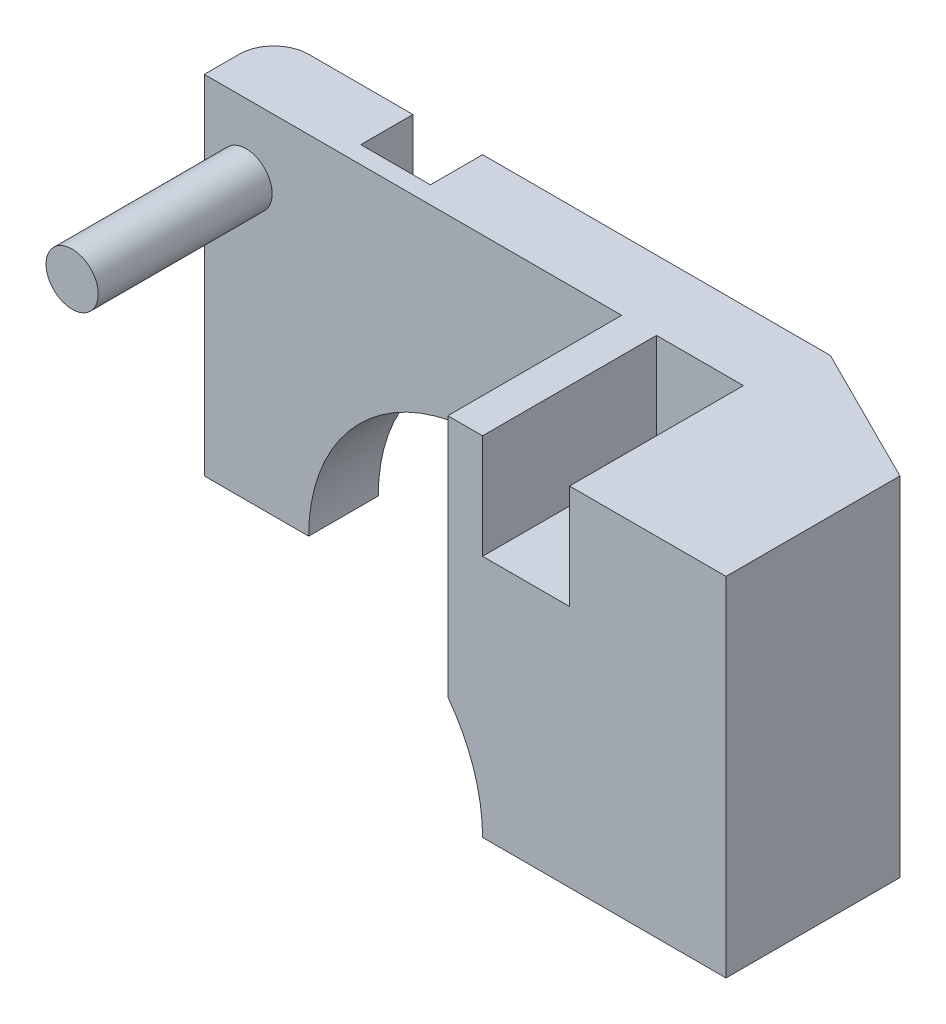
SolidWorks part; units mm, degrees
ref_plane "Přední rovina" through (0, 0, 0) normal (0, 0, 1) x (1, 0, 0)
ref_plane "Horní rovina" through (0, 0, 0) normal (0, 1, 0) x (1, 0, 0)
ref_plane "Pravá rovina" through (0, 0, 0) normal (1, 0, 0) x (0, 0, -1)
sketch "Skica1" plane through (0, 0, 0) normal (0, 0, 1) x (1, 0, 0)
  line L1 (0, 0) -> (200, 0)
  line L2 (0, 0) -> (0, 100)
  line L3 (0, 100) -> (200, 100)
  line L4 (200, 0) -> (200, 100)
  dimension "D1" = 100
  dimension "D2" = 200
extrude "Přidat vysunutím1" add sketch "Skica1" along normal blind 20
sketch "Skica2" plane through (0, 0, 20) normal (0, 0, 1) x (1, 0, 0)
  line L0 (0, 0) -> (200, 0) construction
  line L1 (120, 0) -> (200, 0)
  line L2 (120, 0) -> (120, 100)
  line L3 (120, 100) -> (130, 100)
  line L6 (0, 100) -> (0, 0) construction
  line L7 (155, 100) -> (200, 100)
  line L9 (130, 100) -> (130, 70)
  line L10 (130, 70) -> (155, 70)
  line L11 (155, 100) -> (155, 70)
  line L12 (200, 0) -> (200, 100)
  dimension "D1" = 120
  dimension "D3" = 10
  dimension "D5" = 30
extrude "Přidat vysunutím2" add sketch "Skica2" along normal blind 50 contours L9 L10 L11 L7 L12 L1 L2 L3
sketch "Skica4" plane through (0, 0, 0) normal (0, 0, -1) x (-1, 0, 0)
  line L0 (0, 0) -> (-200, 0) construction
  circle A0 centre (-80, 0) radius 50
  dimension "D1" = 100
  dimension "D2" = 80
extrude "Odebrat vysunutím1" cut sketch "Skica4" against normal up to surface (70 mm away) up to face at (151.25, 67.5, 70)
sketch "Skica7" plane through (0, 0, 20) normal (0, 0, 1) x (1, 0, 0)
  line L0 (120, 100) -> (0, 100) construction
  line L2 (0, 100) -> (0, 0) construction
  circle A0 centre (12, 80) radius 7.5
  dimension "D1" = 15
  dimension "D2" = 20
  dimension "D3" = 12
extrude "Přidat vysunutím3" add sketch "Skica7" along normal blind 50
ref_plane "Rovina1" through (50, 0, 0) normal (-1, 0, 0) x (0, 0, 1)
sketch "Skica8" plane through (50, 0, 0) normal (-1, 0, 0) x (0, 0, 1)
  line L0 (0, 100) -> (0, 0) construction
  line L1 (20, 100) -> (0, 100) construction
  line L2 (0, 100) -> (0, 70)
  line L3 (15, 100) -> (0, 100)
  line L4 (15, 100) -> (0, 70)
  point P5 (0, 0)
  point P6 (0, 0)
  dimension "D1" = 30
  dimension "D2" = 15
extrude "Odebrat vysunutím3" cut sketch "Skica8" against normal mid plane 20 contours L3 L2 L4
fillet "Zaoblit1" radius 10 1 edges at (0, 50, 0)
chamfer "Zkosení1" distance 40 distance2 20 1 edges at (200, 50, 0)
sketch "Skica9" plane through (0, 0, 0) normal (0, 0, -1) x (-1, 0, 0)
  line L0 (-160, 100) -> (-60, 100) construction
  line L1 (-70, 90) -> (-110, 90)
  line L2 (-70, 90) -> (-70, 65)
  line L3 (-70, 65) -> (-110, 65)
  line L4 (-110, 90) -> (-110, 65)
  line L5 (-60, 100) -> (-60, 70) construction
  dimension "D1" = 10
  dimension "D2" = 35
  dimension "D3" = 10
  dimension "D4" = 40
extrude "Odebrat vysunutím4" cut sketch "Skica9" against normal blind 5
